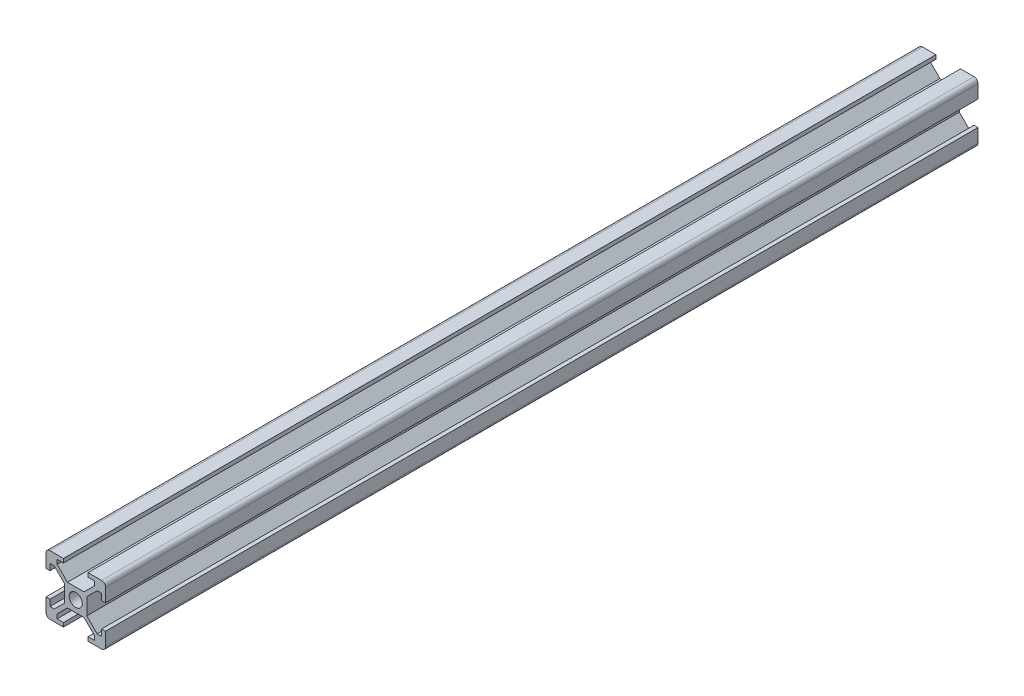
SolidWorks part; units mm, degrees
ref_plane "前视基准面" through (0, 0, 0) normal (0, 0, 1) x (1, 0, 0)
ref_plane "上视基准面" through (0, 0, 0) normal (0, 1, 0) x (1, 0, 0)
ref_plane "右视基准面" through (0, 0, 0) normal (1, 0, 0) x (0, 0, -1)
sketch "草图2" plane through (0, 0, 0) normal (0, 0, 1) x (1, 0, 0)
  line L1 (-2.0929, -2.8) -> (-4.7, -5.4071)
  line L2 (2.8, -2.0929) -> (2.8, 2.0929)
  line L3 (2.8, 2.0929) -> (5.4071, 4.7)
  line L4 (5.4071, 4.7) -> (6.5, 4.7)
  line L5 (6.5, 4.7) -> (6.5, 3.1)
  line L6 (6.5, 3.1) -> (7.5, 3.1)
  line L7 (7.5, 3.1) -> (7.5, 6.5)
  line L8 (-2.8, -2.0929) -> (-5.4071, -4.7)
  line L9 (-2.0929, 2.8) -> (2.0929, 2.8)
  line L10 (3.1, 7.5) -> (6.5, 7.5)
  line L11 (3.1, 6.5) -> (3.1, 7.5)
  line L12 (4.7, 6.5) -> (3.1, 6.5)
  line L13 (4.7, 5.4071) -> (4.7, 6.5)
  line L14 (2.0929, 2.8) -> (4.7, 5.4071)
  line L15 (-5.4071, 4.7) -> (-6.5, 4.7)
  line L16 (-6.5, 4.7) -> (-6.5, 3.1)
  line L17 (-6.5, 3.1) -> (-7.5, 3.1)
  line L18 (-7.5, 3.1) -> (-7.5, 6.5)
  line L19 (-4.7, 6.5) -> (-3.1, 6.5)
  line L20 (-3.1, 6.5) -> (-3.1, 7.5)
  line L21 (-3.1, 7.5) -> (-6.5, 7.5)
  line L22 (-4.7, 5.4071) -> (-4.7, 6.5)
  line L23 (-2.8, 2.0929) -> (-5.4071, 4.7)
  line L24 (-2.8, -2.0929) -> (-2.8, 2.0929)
  line L25 (-2.0929, 2.8) -> (-4.7, 5.4071)
  line L26 (-4.7, -5.4071) -> (-4.7, -6.5)
  line L27 (-3.1, -7.5) -> (-6.5, -7.5)
  line L28 (-3.1, -6.5) -> (-3.1, -7.5)
  line L29 (-4.7, -6.5) -> (-3.1, -6.5)
  line L30 (-7.5, -3.1) -> (-7.5, -6.5)
  line L31 (-6.5, -3.1) -> (-7.5, -3.1)
  line L32 (-6.5, -4.7) -> (-6.5, -3.1)
  line L33 (-5.4071, -4.7) -> (-6.5, -4.7)
  line L34 (2.0929, -2.8) -> (4.7, -5.4071)
  line L35 (4.7, -5.4071) -> (4.7, -6.5)
  line L36 (4.7, -6.5) -> (3.1, -6.5)
  line L37 (3.1, -6.5) -> (3.1, -7.5)
  line L38 (3.1, -7.5) -> (6.5, -7.5)
  line L39 (-2.0929, -2.8) -> (2.0929, -2.8)
  line L40 (7.5, -3.1) -> (7.5, -6.5)
  line L41 (6.5, -3.1) -> (7.5, -3.1)
  line L42 (6.5, -4.7) -> (6.5, -3.1)
  line L43 (5.4071, -4.7) -> (6.5, -4.7)
  line L44 (2.8, -2.0929) -> (5.4071, -4.7)
  arc A0 (7.5, 6.5) -> (6.5, 7.5) centre (6.5, 6.5) ccw
  arc A1 (-7.5, 6.5) -> (-6.5, 7.5) centre (-6.5, 6.5) cw
  arc A2 (-7.5, -6.5) -> (-6.5, -7.5) centre (-6.5, -6.5) ccw
  arc A3 (7.5, -6.5) -> (6.5, -7.5) centre (6.5, -6.5) cw
  circle A4 centre (0, 0) radius 1.65
  point P3 (0, -2.8)
  point P21 (7.5, 7.5)
  point P36 (0, 2.8)
  point P43 (-2.8, 0)
  point P60 (2.8, 0)
  point P61 (7.5, -7.5)
  dimension "D9" = 1
  dimension "D1" = 3.3
  dimension "D5" = 1
  dimension "D8" = 1
extrude "凸台-拉伸1" add sketch "草图2" along normal mid plane 220
